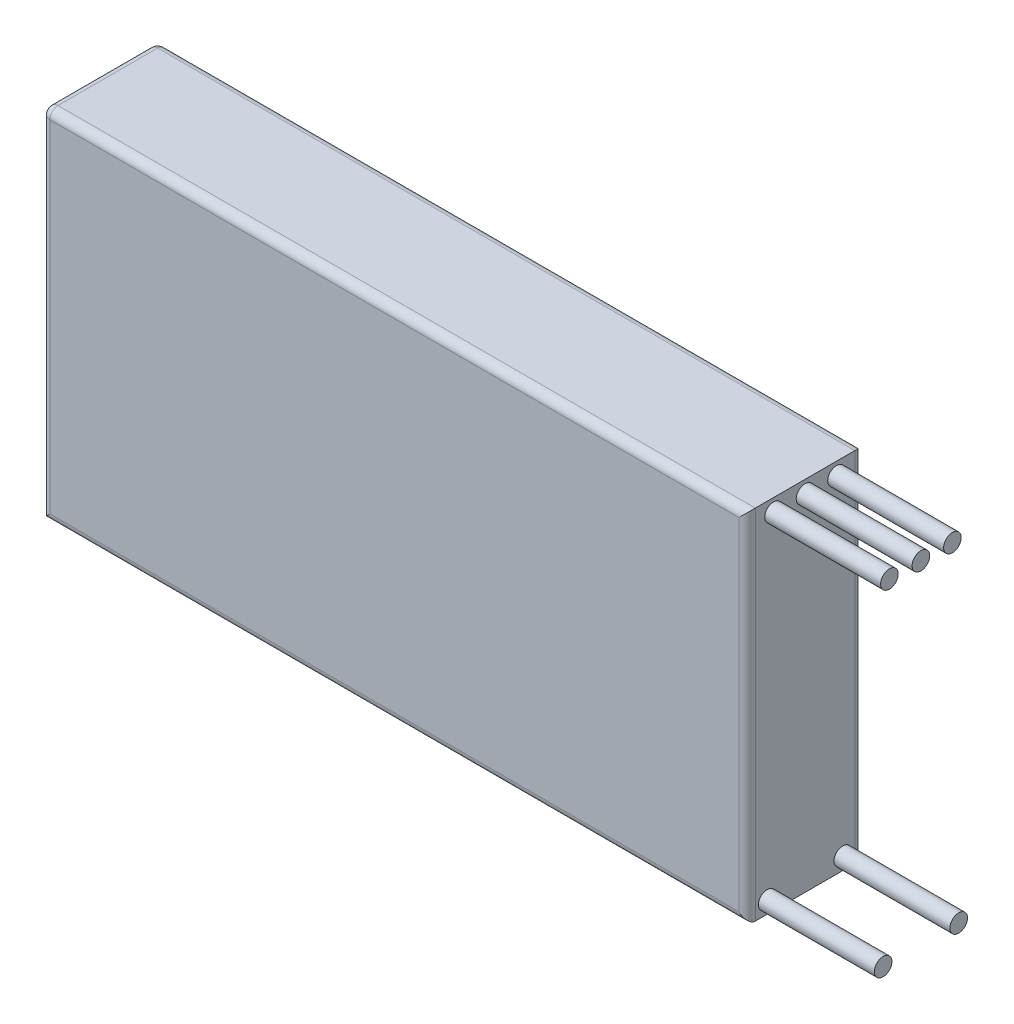
SolidWorks part; units mm, degrees
ref_plane "Front Plane" through (0, 0, 0) normal (0, 0, 1) x (1, 0, 0)
ref_plane "Top Plane" through (0, 0, 0) normal (0, 1, 0) x (1, 0, 0)
ref_plane "Right Plane" through (0, 0, 0) normal (1, 0, 0) x (0, 0, -1)
sketch "Sketch1" plane through (0, 0, 0) normal (0, 0, 1) x (1, 0, 0)
  line L1 (0, 0) -> (71.12, 0)
  line L2 (0, 0) -> (0, 36.068)
  line L3 (0, 36.068) -> (71.12, 36.068)
  line L4 (71.12, 0) -> (71.12, 36.068)
  dimension "D1" = 71.12
  dimension "D2" = 36.068
extrude "Boss-Extrude1" add sketch "Sketch1" along normal blind 11.684
sketch "Sketch2" plane through (71.12, 0, 0) normal (1, 0, 0) x (0, 0, -1)
  line L0 (-9.652, 1.27) -> (-2.032, 1.27) construction
  line L1 (-5.842, 1.27) -> (-5.842, 0) construction
  line L2 (-11.684, 0) -> (0, 0) construction
  line L3 (-9.017, 34.798) -> (-5.842, 34.798) construction
  line L4 (-5.842, 34.798) -> (-2.667, 34.798) construction
  line L5 (-5.842, 34.798) -> (-5.842, 36.068) construction
  line L6 (-11.684, 36.068) -> (0, 36.068) construction
  circle A0 centre (-9.652, 1.27) radius 0.889
  circle A1 centre (-2.032, 1.27) radius 0.889
  circle A2 centre (-9.017, 34.798) radius 0.889
  circle A3 centre (-5.842, 34.798) radius 0.889
  circle A4 centre (-2.667, 34.798) radius 0.889
  point P17 (-5.842, 34.2852)
  dimension "D1" = 1.778
  dimension "D2" = 1.778
  dimension "D3" = 7.62
  dimension "D4" = 1.27
  dimension "D5" = 6.35
  dimension "D6" = 1.27
extrude "Boss-Extrude2" add sketch "Sketch2" along normal blind 11.684
fillet "Fillet1" radius 0.8255 9 edges at (35.56, 0, 0) (71.12, 18.034, 0) (35.56, 36.068, 0) (0, 18.034, 0) (35.56, 36.068, 11.684) (71.12, 18.034, 11.684) (35.56, 0, 11.684) (0, 18.034, 11.684) (0, 36.068, 5.842)
